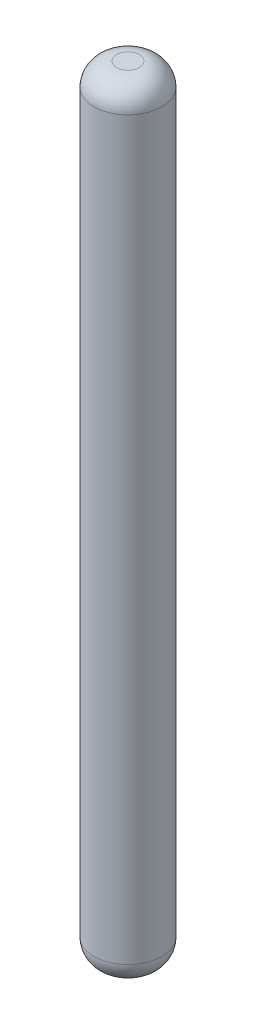
SolidWorks part; units mm, degrees
ref_plane "Front Plane" through (0, 0, 0) normal (0, 0, 1) x (1, 0, 0)
ref_plane "Top Plane" through (0, 0, 0) normal (0, 1, 0) x (1, 0, 0)
ref_plane "Right Plane" through (0, 0, 0) normal (1, 0, 0) x (0, 0, -1)
sketch "Sketch1" plane through (0, 0, 0) normal (0, 1, 0) x (1, 0, 0)
  circle A0 centre (0, 0) radius 1.5
  dimension "D1" = 3
extrude "Boss-Extrude1" add sketch "Sketch1" along normal blind 34.5
fillet "Fillet1" radius 1 2 edges at (0, 34.5, 1.5) (0, 0, 1.5)
